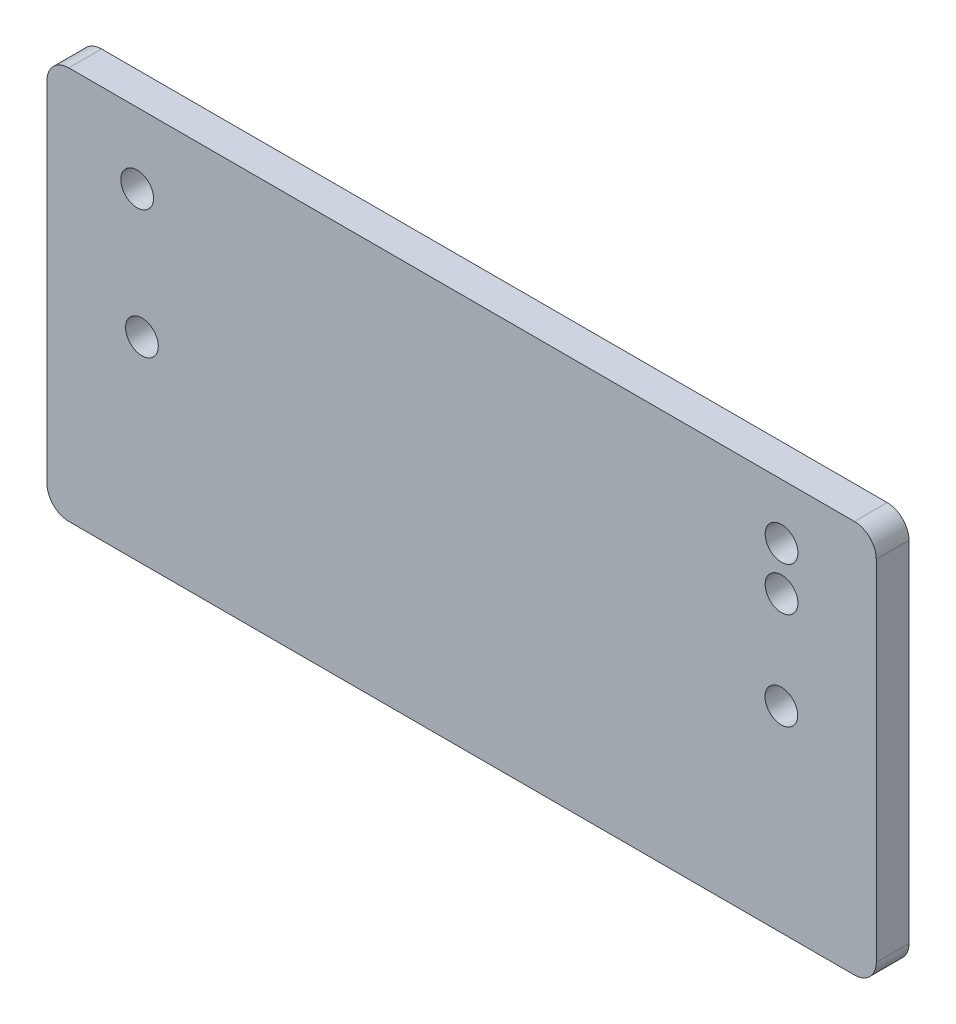
SolidWorks part; units mm, degrees
material "PBT 一般用途"
ref_plane "前视基准面" through (0, 0, 0) normal (0, 0, 1) x (1, 0, 0)
ref_plane "上视基准面" through (0, 0, 0) normal (0, 1, 0) x (1, 0, 0)
ref_plane "右视基准面" through (0, 0, 0) normal (1, 0, 0) x (0, 0, -1)
other "Configuration Table"
sketch "草图1" plane through (0, 0, 0) normal (0, 0, 1) x (1, 0, 0)
  line L0 (-31.3241, 0) -> (40.6759, 0)
  line L1 (-33.3241, -2) -> (-33.3241, -34)
  line L2 (-31.3241, -36) -> (40.6759, -36)
  line L3 (42.6759, -34) -> (42.6759, -2)
  arc A0 (40.6759, 0) -> (42.6759, -2) centre (40.6759, -2) cw
  arc A1 (42.6759, -34) -> (40.6759, -36) centre (40.6759, -34) cw
  arc A2 (-31.3241, -36) -> (-33.3241, -34) centre (-31.3241, -34) cw
  arc A3 (-33.3241, -2) -> (-31.3241, 0) centre (-31.3241, -2) cw
  point P7 (42.6759, 0)
  point P12 (-33.3241, -36)
  point P15 (-33.3241, 0)
  dimension "D3" = 2
  dimension "D1" = 36
  dimension "D2" = 76
extrude "凸台-拉伸1" add sketch "草图1" along normal blind 3
sketch "草图2" plane through (0, 0, 3) normal (0, 0, 1) x (1, 0, 0)
  line L0 (40.6759, 0) -> (-31.3241, 0) construction
  line L1 (-33.3241, -2) -> (-33.3241, -34) construction
  circle A0 centre (-24.6241, -18) radius 1.5
  circle A1 centre (33.9759, -18) radius 1.5
  circle A5 centre (-25.0626, -6.477) radius 1.5
  circle A6 centre (33.9924, -5.08) radius 1.5
  circle A7 centre (33.9924, -9.08) radius 1.5
  point P0 (-24.6241, -18)
  point P5 (33.9759, -18)
  point P12 (-25.0626, -6.477)
  point P14 (33.9924, -5.08)
  point P15 (33.9924, -9.08)
  dimension "D4" = 6.477
  dimension "D7" = 5.08
  dimension "D1" = 18
  dimension "D2" = 8.7
  dimension "D3" = 58.6
  dimension "D5" = 59.055
  dimension "D6" = 4
extrude "切除-拉伸1" cut sketch "草图2" against normal blind 3
